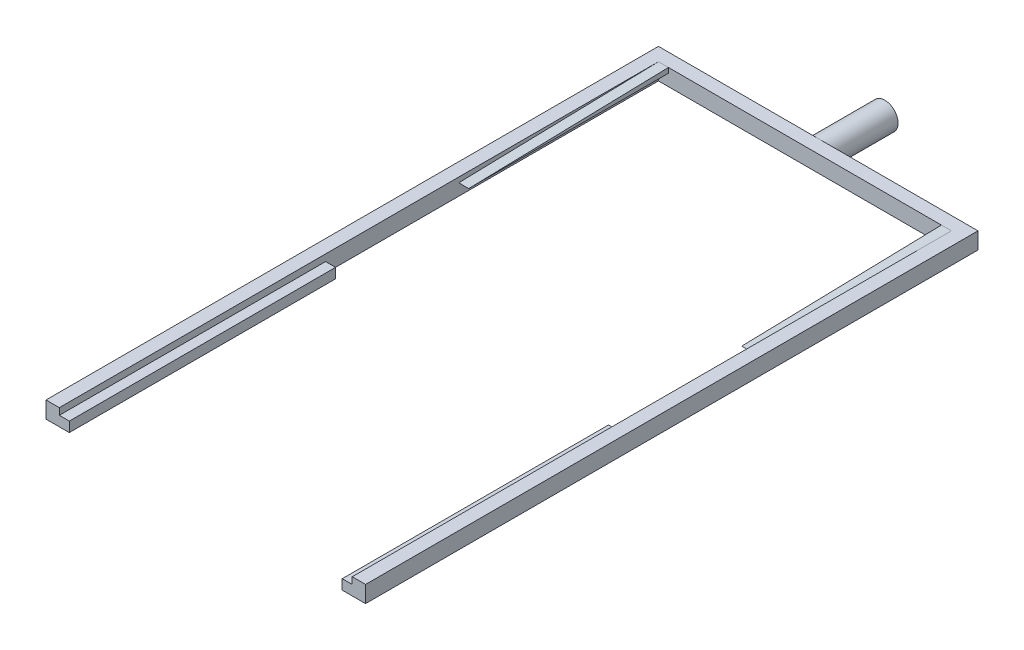
SolidWorks part; units mm, degrees
ref_plane "Front Plane" through (0, 0, 0) normal (0, 0, 1) x (1, 0, 0)
ref_plane "Top Plane" through (0, 0, 0) normal (0, 1, 0) x (1, 0, 0)
ref_plane "Right Plane" through (0, 0, 0) normal (1, 0, 0) x (0, 0, -1)
sketch "Sketch2" plane through (0, 0, 0) normal (0, 1, 0) x (1, 0, 0)
  line L0 (-22, -45) -> (-22, 45)
  line L1 (-22, 45) -> (22, 45)
  line L2 (22, -45) -> (22, 45)
  line L3 (0, 45) -> (0, 6.9066) construction
  line L4 (-22, 0) -> (22, 0) construction
  line L5 (-24, -45) -> (-24, 47)
  line L6 (-24, 47) -> (24, 47)
  line L7 (24, -45) -> (24, 47)
  line L8 (-24, -45) -> (-22, -45)
  line L9 (22, -45) -> (24, -45)
  dimension "D1" = 44
  dimension "D2" = 90
  dimension "D3" = 90
  dimension "D4" = 2
extrude "Boss-Extrude1" add sketch "Sketch2" along normal blind 2.5 contours L5 L6 L7 L9 L2 L1 L0 L8
sketch "Sketch4" plane through (-22, 0, 0) normal (1, 0, 0) x (0, 0, -1)
  line L0 (45, 1.75) -> (15, 1.75)
  line L1 (45, 2.5) -> (45, 0) construction
  line L2 (15, 1.75) -> (45, 2.5)
  line L3 (45, 2.5) -> (45, 1.75)
  line L4 (-45, 0) -> (-5, 0)
  line L5 (-45, 0) -> (47, 0) construction
  line L6 (-5, 0) -> (-5, 1.5)
  line L7 (-5, 1.5) -> (-45, 1.5)
  line L8 (-45, 2.5) -> (-45, 0) construction
  line L9 (-45, 1.5) -> (-45, 0)
  line L10 (-45, 2.5) -> (47, 2.5) construction
  point P16 (0, 0)
  dimension "D1" = 40
  dimension "D2" = 1.5
  dimension "D4" = 0.25
  dimension "D5" = 60
extrude "Boss-Extrude3" add sketch "Sketch4" along normal blind 1.5
mirror "Mirror1" about plane through (0, 0, 0) normal (1, 0, 0) of "Boss-Extrude3"
sketch "Sketch6" plane through (0, 0, -47) normal (0, 0, -1) x (-1, 0, 0)
  line L0 (0, 55) -> (0, -55) construction
  line L1 (-24, 1.25) -> (24, 1.25) construction
  line L2 (-24, 2.5) -> (-24, 0) construction
  line L3 (24, 2.5) -> (24, 0) construction
  line L5 (24, 2.5) -> (-24, 2.5) construction
  circle A0 centre (0, 0.5) radius 2
  point P10 (0, 0)
  dimension "D1" = 4
extrude "Boss-Extrude4" add sketch "Sketch6" along normal blind 10 contours A0
